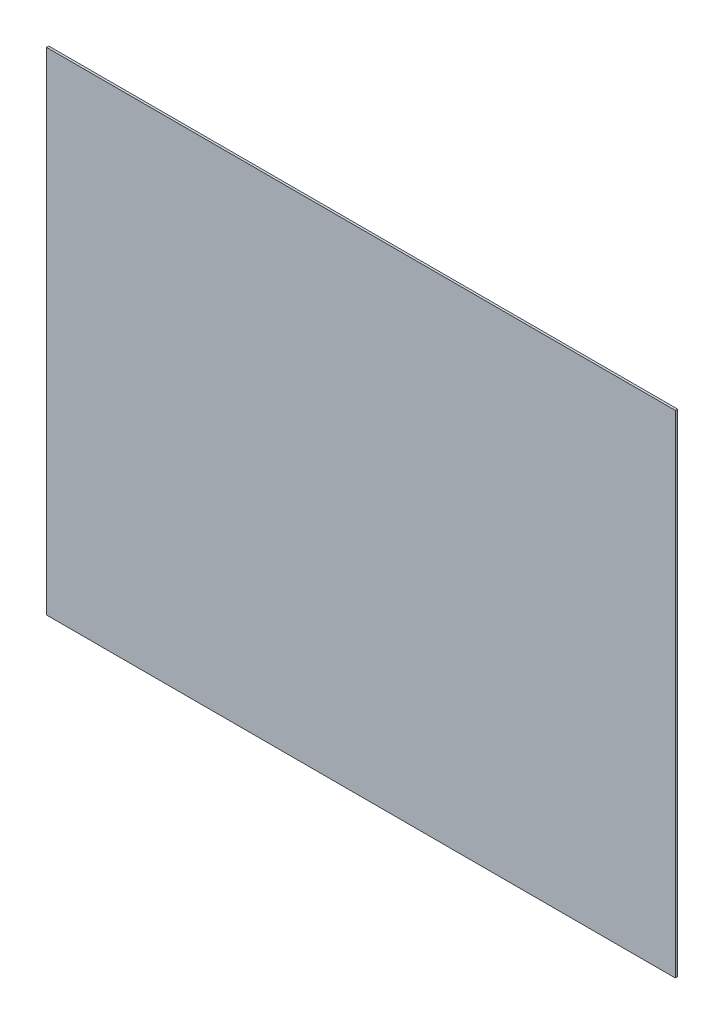
SolidWorks part; units mm, degrees
material "Chapa F.F 1020 - 1,5 mm"
ref_plane "Plano frontal" through (0, 0, 0) normal (0, 0, 1) x (1, 0, 0)
ref_plane "Plano superior" through (0, 0, 0) normal (0, 1, 0) x (1, 0, 0)
ref_plane "Plano direito" through (0, 0, 0) normal (1, 0, 0) x (0, 0, -1)
sketch "Esboço1" plane through (0, 0, 0) normal (0, 0, 1) x (1, 0, 0)
  line L1 (0, 0) -> (550, 0)
  line L2 (0, 0) -> (0, 430)
  line L3 (0, 430) -> (550, 430)
  line L4 (550, 0) -> (550, 430)
  dimension "D1" = 430
  dimension "D2" = 550
extrude "Ressalto-extrusão1" add sketch "Esboço1" along normal blind 2
